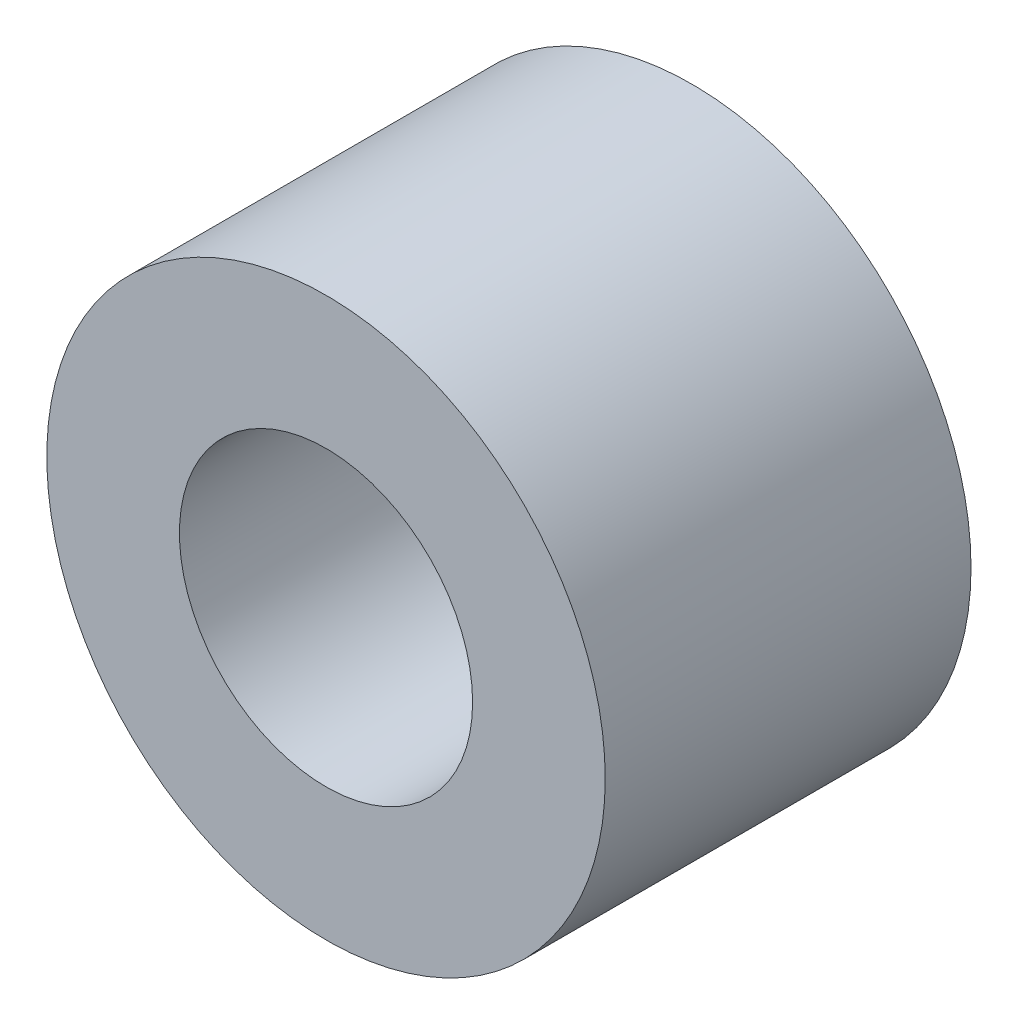
SolidWorks part; units mm, degrees
ref_plane "Plan de face" through (0, 0, 0) normal (0, 0, 1) x (1, 0, 0)
ref_plane "Plan de dessus" through (0, 0, 0) normal (0, 1, 0) x (1, 0, 0)
ref_plane "Plan de droite" through (0, 0, 0) normal (1, 0, 0) x (0, 0, -1)
sketch "Esquisse1" plane through (0, 0, 0) normal (0, 0, 1) x (1, 0, 0)
  circle A0 centre (0, 0) radius 2
  circle A1 centre (0, 0) radius 1.05
  dimension "D1" = 4
extrude "Boss.-Extru.1" add sketch "Esquisse1" along normal blind 2.62
